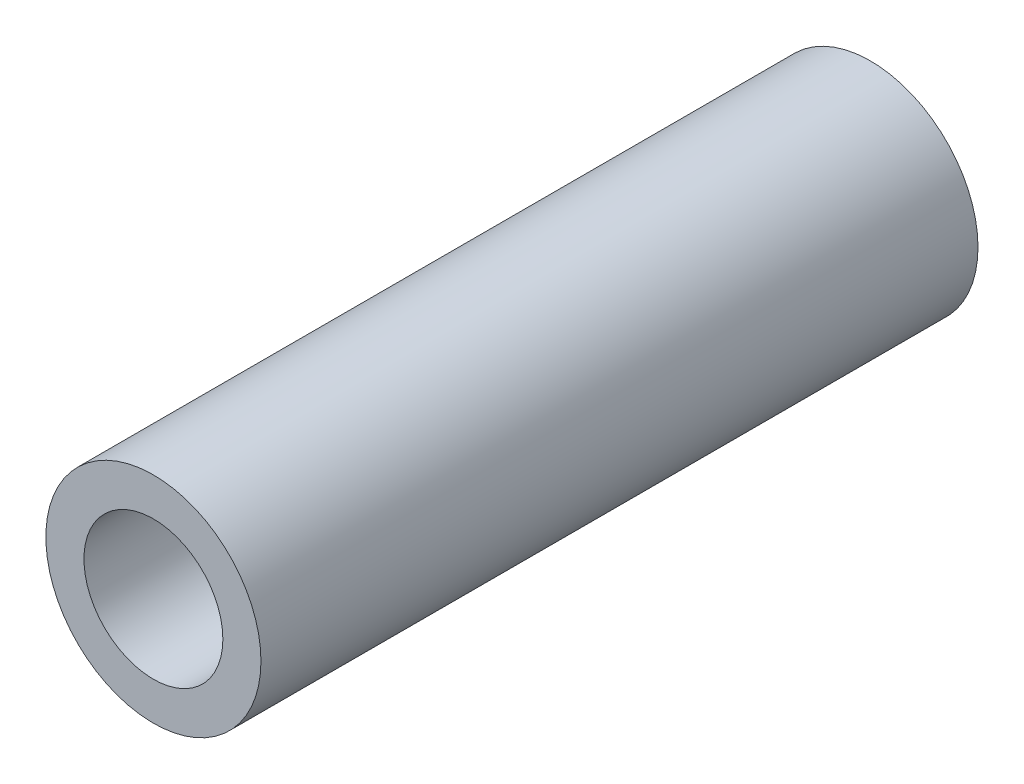
SolidWorks part; units mm, degrees
ref_plane "Front Plane" through (0, 0, 0) normal (0, 0, 1) x (1, 0, 0)
ref_plane "Top Plane" through (0, 0, 0) normal (0, 1, 0) x (1, 0, 0)
ref_plane "Right Plane" through (0, 0, 0) normal (1, 0, 0) x (0, 0, -1)
sketch "Sketch1" plane through (0, 0, 0) normal (0, 0, 1) x (1, 0, 0)
  circle A0 centre (-33.893, 10.6703) radius 2.4
  circle A1 centre (-33.893, 10.6703) radius 1.55
extrude "Boss-Extrude1" add sketch "Sketch1" along normal blind 16
